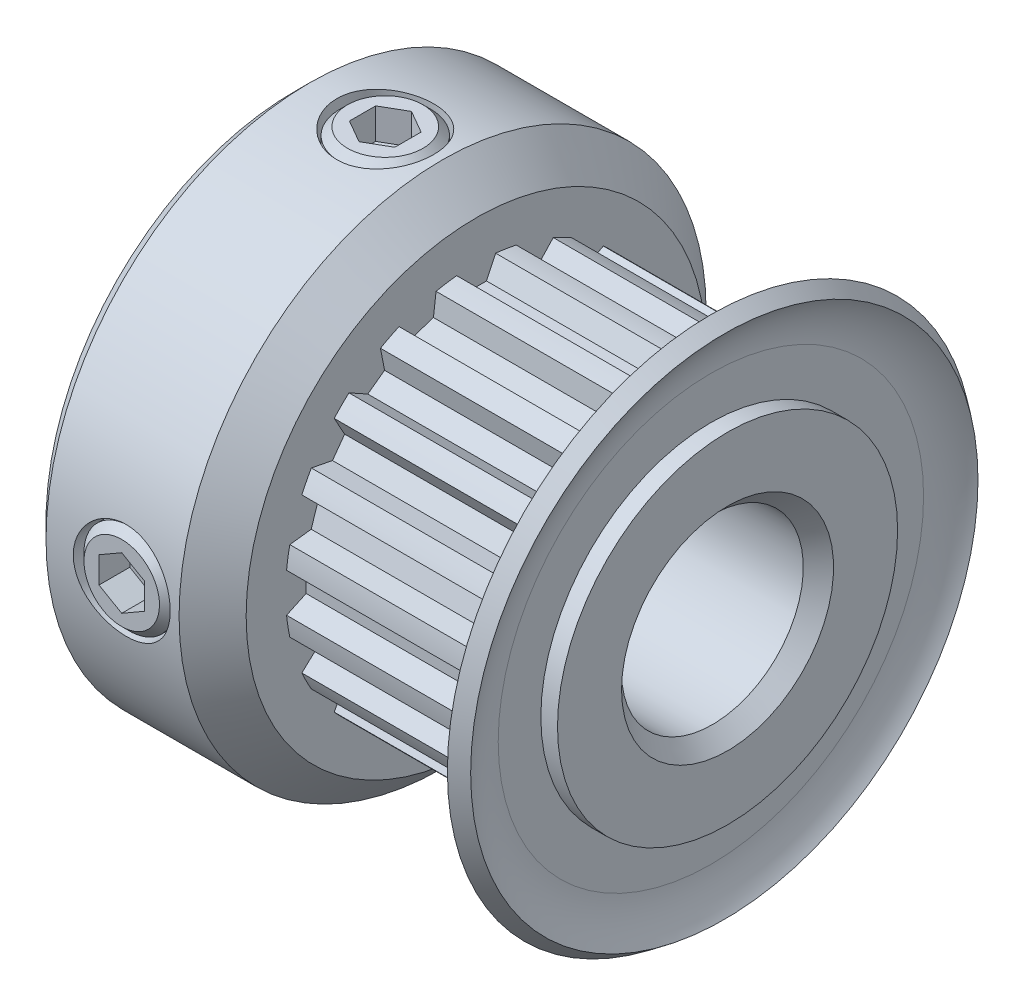
SolidWorks part; units mm, degrees
ref_plane "Front Plane" through (0, 0, 0) normal (0, 0, 1) x (1, 0, 0)
ref_plane "Top Plane" through (0, 0, 0) normal (0, 1, 0) x (1, 0, 0)
ref_plane "Right Plane" through (0, 0, 0) normal (1, 0, 0) x (0, 0, -1)
sketch "Sketch2" plane through (0, 0, 0) normal (1, 0, 0) x (0, 0, -1)
  line L3 (0, 0) -> (0, 5.6245) construction
  line L6 (0, -6.1325) -> (0, -6.45) construction
  line L7 (-0.5715, 6.1058) -> (-0.3422, 5.6141)
  line L8 (0.5715, 6.1058) -> (0.3422, 5.6141)
  line L9 (-0.5715, 6.1058) -> (-0.6426, 6.2583)
  line L10 (0.5715, 6.1058) -> (0.6426, 6.2583)
  line L12 (-0.3422, 5.6141) -> (0.3422, 5.6141)
  line L14 (0, 6.1325) -> (0, 6.45) construction
  line L15 (0, 0) -> (0, -1.143) construction
  circle A0 centre (0, 0) radius 6.45 construction
  circle A1 centre (0, 0) radius 5.6245 construction
  circle A2 centre (0, 0) radius 6.1325 construction
  arc A7 (0.6426, 6.2583) -> (-0.6426, 6.2583) centre (0, 0) ccw
  point P5 (0, 6.2912)
  dimension "D3" = 0.3175
  dimension "D1" = 50
sketch "Sketch1" plane through (0, 0, 0) normal (0, 0, 1) x (1, 0, 0)
  line L0 (-7.15, 0) -> (7.15, 0) construction
  line L1 (-7.15, 3) -> (7.15, 3)
  line L2 (-7.15, 3) -> (-7.15, 8.7)
  line L3 (-7.15, 8.7) -> (-2.257, 8.7)
  line L4 (-2.257, 8.7) -> (-1.15, 7.593)
  line L5 (-1.15, 7.593) -> (-1.15, 6.45)
  line L6 (-1.15, 6.45) -> (6.05, 6.45)
  line L7 (6.05, 6.45) -> (6.05, 7.0215)
  line L8 (6.05, 6.45) -> (7.15, 6.45) construction
  line L9 (6.6, 8.7) -> (7.15, 8.7)
  line L10 (7.15, 8.7) -> (7.15, 3)
  line L11 (6.6, 6.45) -> (6.6, 8.7) construction
  line L12 (-4.7035, 8.7) -> (-4.7035, 3) construction
  arc A0 (6.05, 7.0215) -> (6.6, 8.7) centre (8.8862, 7.0215) cw
  dimension "Bore Size" = 6
  dimension "Overall Width" = 14.3
  dimension "Inside Width" = 7.2
  dimension "Outside Width" = 8.3
  dimension "Hub Dia" = 17.4
  dimension "OD" = 17.4
  dimension "D1" = 45
  dimension "D2" = 12.9
  dimension "D3" = 1.143
  dimension "D4" = 0.5715
revolve "Revolve1" add sketch "Sketch1" angle 360 mid plane about L0
sketch "Sketch4" plane through (-1.15, 0, 0) normal (1, 0, 0) x (0, 0, -1)
  circle A0 centre (0, 0) radius 6.2912
  circle A1 centre (0, 0) radius 6.45 construction
  circle A2 centre (0, 0) radius 6.45
extrude "Cut-Extrude2" cut sketch "Sketch4" along normal up to surface (7.2 mm away) up to face at (6.05, 0, 6.45)
sketch "Sketch3" plane through (-1.15, 0, 0) normal (1, 0, 0) x (0, 0, -1)
  line L2 (-0.5715, 6.1058) -> (-0.3422, 5.6141) construction
  line L3 (-0.3422, 5.6141) -> (0.3422, 5.6141) construction
  line L4 (0.5715, 6.1058) -> (0.3422, 5.6141) construction
  line L5 (-0.6426, 6.2583) -> (-0.3422, 5.6141)
  line L6 (-0.3422, 5.6141) -> (0.3422, 5.6141)
  line L7 (0.6426, 6.2583) -> (0.3422, 5.6141)
  arc A1 (0.6426, 6.2583) -> (-0.6426, 6.2583) centre (0, 0) ccw construction
  arc A2 (0.6426, 6.2583) -> (-0.6426, 6.2583) centre (0, 0) ccw
extrude "Cut-Extrude1" cut sketch "Sketch3" along normal up to surface (7.2 mm away)
pattern_circular "CirPattern1" count 20 over 360 about axis through (0, 0, 0) along (1, 0, 0) of "Cut-Extrude1"
sketch "Sketch5" plane through (0, 0, 0) normal (0, 1, 0) x (1, 0, 0)
  line L0 (-7.15, 8.7) -> (-7.15, -8.7) construction
  line L1 (6.05, 7.0215) -> (6.05, -7.0215) construction
  line L2 (7.15, 8.7) -> (7.15, -8.7) construction
  line L3 (-1.15, 7.593) -> (-1.15, -7.593) construction
  line L4 (6.05, 7.0215) -> (6.05, -7.0215) construction
  line L5 (-7.15, 0) -> (7.15, 0) construction
  line L6 (-7.15, 0) -> (7.15, 0) construction
  point P0 (6.05, 0)
  point P14 (6.05, 0)
  point P15 (-1.15, 0)
  dimension "D1" = 17.4
  dimension "D2" = 17.4
sketch "Sketch6" plane through (0, 0, 0) normal (0, 1, 0) x (1, 0, 0)
  line L0 (-7.15, 0) -> (-5.65, 0) construction
  line L1 (-7.15, 8.7) -> (-7.15, -8.7) construction
  line L2 (-1.15, 0) -> (-2.65, 0) construction
  line L3 (-1.15, -0.3422) -> (-1.15, 0.3422) construction
  line L4 (-5.65, 0) -> (-4.15, 0) construction
  line L5 (-4.15, 0) -> (-5.2107, -1.0607) construction
  circle A0 centre (-4.15, 0) radius 1.5 construction
  circle A1 centre (-4.15, 0) radius 1.6
  point P13 (-5.2107, -1.0607)
  dimension "D1" = 0.1
  dimension "D2" = 45
  dimension "SS Dia" = 3
extrude "Cut-Extrude3" cut sketch "Sketch6" along normal through all
sketch "Sketch7" plane through (0, 0, 0) normal (0, 0, 1) x (1, 0, 0)
  line L0 (-5.396, 8.7) -> (-4.15, 8.7)
  line L1 (-5.65, 8.446) -> (-5.65, 3.635)
  line L2 (-5.65, 3.635) -> (-5.396, 3.381)
  line L3 (-5.396, 3.381) -> (-4.15, 3.381)
  line L4 (-4.15, 3.381) -> (-4.15, 8.7) construction
  line L6 (-5.65, 8.446) -> (-5.396, 8.7)
  line L7 (-7.15, 8.7) -> (-2.257, 8.7) construction
  line L8 (-4.15, 8.7) -> (-4.15, 3.381)
  point P0 (-5.65, 8.7)
  point P4 (-5.65, 3.381)
  dimension "D2" = 0.381
revolve "Revolve2" add sketch "Sketch7" angle 360 mid plane about L4
sketch "Sketch8" plane through (0, 8.7, 0) normal (0, 1, 0) x (1, 0, 0)
  line L0 (-4.15, 0) -> (-5.65, 0) construction
  line L1 (-4.15, 0.866) -> (-4.9, 0.433)
  line L2 (-4.9, 0.433) -> (-4.9, -0.433)
  line L3 (-4.9, -0.433) -> (-4.15, -0.866)
  line L4 (-4.15, -0.866) -> (-3.4, -0.433)
  line L5 (-3.4, -0.433) -> (-3.4, 0.433)
  line L6 (-3.4, 0.433) -> (-4.15, 0.866)
  circle A0 centre (-4.15, 0) radius 0.75 construction
  point P13 (-4.9, 0)
extrude "Cut-Extrude4" cut sketch "Sketch8" against normal blind 1.016
pattern_circular "CirPattern2" count 2 over 90 about axis through (-7.15, 0, 0) along (-1, 0, 0) of "Cut-Extrude3"
pattern_circular "CirPattern3" count 2 over 90 about axis through (0, 0, 0) along (1, 0, 0) of bodies 107
chamfer "Chamfer1" distance 0.5 angle 45 3 edges at (-7.15, 0, 8.7) (-7.15, 0, 3) (7.15, 0, 3)
sketch "Sketch9" plane through (0, 0, 0) normal (0, 0, 1) x (1, 0, 0)
  line L0 (7.15, 5.6141) -> (7.15, 8.7)
  line L1 (7.15, 8.7) -> (7.15, 3) construction
  line L2 (6.6, 6.45) -> (6.6, 8.7) construction
  line L3 (6.6, 7.0215) -> (6.6, 5.6141)
  line L4 (6.6, 8.7) -> (6.7926, 8.9624)
  line L5 (6.6, 5.6141) -> (7.15, 5.6141)
  line L6 (6.6, 8.7) -> (7.0433, 8.3745)
  line L7 (6.7926, 8.9624) -> (7.15, 8.7)
  line L8 (-1.15, 5.6141) -> (7.15, 5.6141) construction
  line L9 (-7.15, 0) -> (7.15, 0) construction
  line L10 (-7.15, 0) -> (7.15, 0) construction
  arc A0 (6.6, 8.7) -> (6.05, 7.0215) centre (8.8862, 7.0215) ccw construction
  arc A3 (6.6, 7.0215) -> (7.0433, 8.3745) centre (8.8862, 7.0215) cw
revolve "Cut-Revolve1" cut sketch "Sketch9" angle 360 about L0
equation "\"D3@Sketch2\" = (\"hs@Sketch2\"-\"ht@Sketch2\")/2"
equation "\"D2@Sketch1\" = \"PD@Sketch2\""
equation "\"D3@Sketch1\" = \"hs@Sketch2\""
equation "\"D4@Sketch1\" = \"D3@Sketch1\"/2"
equation "\"D1@Sketch5\"=\"Hub Dia@Sketch1\""
equation "\"D2@Sketch5\"=\"OD@Sketch1\""
